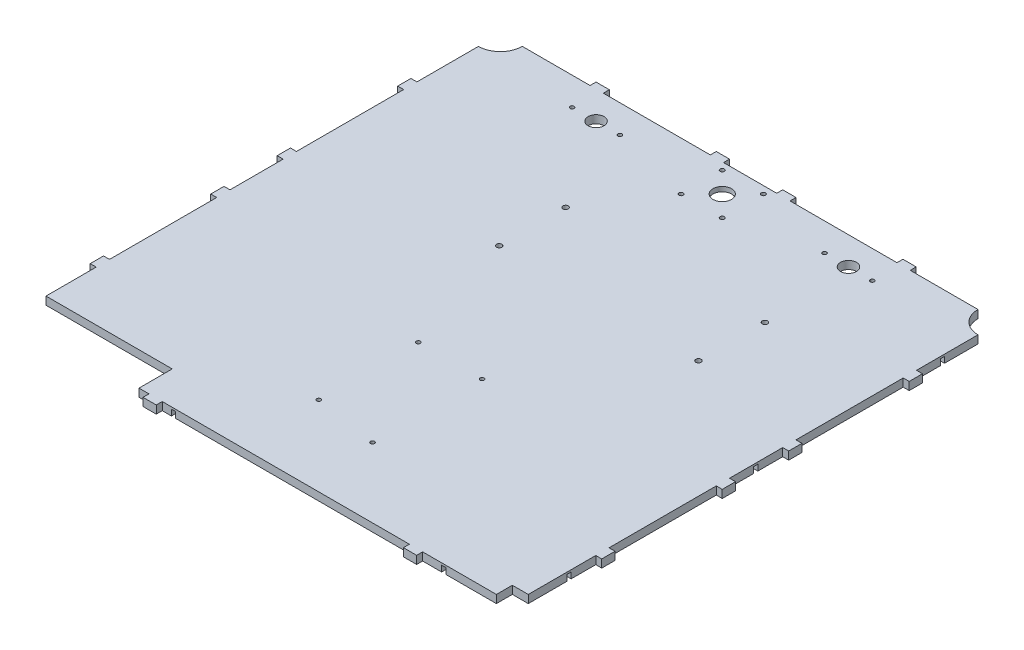
SolidWorks part; units mm, degrees
ref_plane "Alzado" through (0, 0, 0) normal (0, 0, 1) x (1, 0, 0)
ref_plane "Planta" through (0, 0, 0) normal (0, 1, 0) x (1, 0, 0)
ref_plane "Vista lateral" through (0, 0, 0) normal (1, 0, 0) x (0, 0, -1)
sketch "Croquis1" plane through (0, 0, 0) normal (0, 1, 0) x (1, 0, 0)
  line L0 (0, 0) -> (67.5, 0)
  line L1 (188, 367) -> (188, 375.2829) construction
  line L4 (77.5, 0) -> (102.5, 0)
  line L5 (0, 0) -> (0, 62.8)
  line L6 (0, 62.8) -> (-4.5, 62.8)
  line L7 (-4.5, 62.8) -> (-4.5, 72.8)
  line L8 (-4.5, 72.8) -> (0, 72.8)
  line L9 (0, 72.8) -> (0, 153.5)
  line L10 (0, 153.5) -> (-4.5, 153.5)
  line L11 (-4.5, 153.5) -> (-4.5, 163.5)
  line L12 (-4.5, 163.5) -> (0, 163.5)
  line L13 (0, 163.5) -> (0, 203.5)
  line L14 (0, 183.5) -> (180.5, 183.5) construction
  line L15 (188, 367) -> (188, 0) construction
  line L16 (-4.5, 203.5) -> (0, 203.5)
  line L17 (-4.5, 213.5) -> (-4.5, 203.5)
  line L18 (0, 213.5) -> (-4.5, 213.5)
  line L19 (0, 294.2) -> (0, 213.5)
  line L20 (-4.5, 294.2) -> (0, 294.2)
  line L21 (-4.5, 304.2) -> (-4.5, 294.2)
  line L22 (0, 304.2) -> (-4.5, 304.2)
  line L23 (0, 304.2) -> (0, 350.5)
  line L24 (16.5, 367) -> (67.5, 367)
  line L25 (67.5, 367) -> (67.5, 371.5)
  line L26 (67.5, 371.5) -> (77.5, 371.5)
  line L27 (77.5, 371.5) -> (77.5, 367)
  line L28 (77.5, 367) -> (158, 367)
  line L29 (158, 367) -> (158, 371.5)
  line L30 (158, 371.5) -> (168, 371.5)
  line L31 (168, 371.5) -> (168, 367)
  line L32 (168, 367) -> (208, 367)
  line L33 (376, 163.5) -> (376, 203.5)
  line L34 (380.5, 163.5) -> (376, 163.5)
  line L35 (380.5, 153.5) -> (380.5, 163.5)
  line L36 (376, 153.5) -> (380.5, 153.5)
  line L37 (376, 72.8) -> (376, 153.5)
  line L38 (380.5, 72.8) -> (376, 72.8)
  line L39 (380.5, 62.8) -> (380.5, 72.8)
  line L40 (376, 62.8) -> (380.5, 62.8)
  line L41 (376, 0) -> (376, 62.8)
  line L42 (298.5, -4.5) -> (298.5, 0)
  line L43 (308.5, -4.5) -> (298.5, -4.5)
  line L44 (308.5, 0) -> (308.5, -4.5)
  line L45 (376, 0) -> (308.5, 0)
  line L46 (208, 371.5) -> (208, 367)
  line L47 (218, 371.5) -> (208, 371.5)
  line L48 (218, 367) -> (218, 371.5)
  line L49 (298.5, 367) -> (218, 367)
  line L50 (298.5, 371.5) -> (298.5, 367)
  line L51 (308.5, 371.5) -> (298.5, 371.5)
  line L52 (308.5, 367) -> (308.5, 371.5)
  line L53 (359.5, 367) -> (308.5, 367)
  line L54 (376, 350.5) -> (376, 304.2)
  line L55 (376, 304.2) -> (380.5, 304.2)
  line L56 (380.5, 304.2) -> (380.5, 294.2)
  line L57 (380.5, 294.2) -> (376, 294.2)
  line L58 (376, 294.2) -> (376, 213.5)
  line L59 (376, 213.5) -> (380.5, 213.5)
  line L60 (380.5, 213.5) -> (380.5, 203.5)
  line L61 (380.5, 203.5) -> (376, 203.5)
  line L62 (102.5, 0) -> (102.5, 14.5062) construction
  line L63 (112.5, 0) -> (298.5, 0)
  line L64 (67.5, 0) -> (77.5, 0)
  line L65 (102.5, 0) -> (102.5, -4.5)
  line L66 (102.5, -4.5) -> (112.5, -4.5)
  line L67 (112.5, 0) -> (112.5, -4.5)
  arc A0 (0, 350.5) -> (16.5, 367) centre (0, 367) ccw
  arc A1 (376, 350.5) -> (359.5, 367) centre (376, 367) cw
  dimension "D8" = 33
  dimension "D14" = 46.3
  dimension "D2" = 20
  dimension "D5" = 62.8
  dimension "D6" = 4.5
  dimension "D7" = 10
  dimension "D9" = 10
  dimension "D10" = 20
  dimension "D11" = 51
  dimension "D12" = 10
  dimension "D13" = 4.5
  dimension "D15" = 10
  dimension "D16" = 16.5
  dimension "D17" = 16.5
  dimension "D18" = 25
  dimension "D19" = 10
extrude "Saliente-Extruir1" add sketch "Croquis1" against normal blind 6
sketch "Croquis3" plane through (0, -6, 0) normal (0, -1, 0) x (1, 0, 0)
  line L0 (324.3519, 0) -> (324.3519, -11.6932) construction
  line L1 (325.9019, -6.5002) -> (325.9019, 0)
  line L2 (327.1922, -8.0283) -> (327.1922, -9.5783)
  line L3 (322.2204, -10.8802) -> (322.3896, -10.8802)
  line L4 (325.9019, 0) -> (322.8019, 0)
  line L5 (321.5115, -8.0283) -> (321.5115, -9.5783)
  line L6 (326.4834, -10.8802) -> (326.3141, -10.8802)
  line L7 (322.8019, -6.5002) -> (322.8019, 0)
  line L9 (324.3519, -11.6932) -> (324.3519, 0.5178) construction
  line L10 (188, 0) -> (188, -367) construction
  line L11 (324.3519, -367) -> (324.3519, -355.3068) construction
  line L12 (208, -367) -> (168, -367) construction
  line L13 (322.8019, -360.4998) -> (322.8019, -367)
  line L14 (6.5002, -322.2809) -> (0, -322.2809)
  line L15 (8.7074, -321.1473) -> (10.2574, -321.1473)
  line L16 (10.8802, -326.1191) -> (10.8802, -326.1066)
  line L17 (0, -322.2809) -> (0, -325.5376)
  line L18 (8.0283, -326.828) -> (9.5783, -326.828)
  line L19 (10.8802, -321.6994) -> (10.8802, -321.8687)
  line L20 (321.5115, -358.9717) -> (321.5115, -357.4217)
  line L21 (6.5002, -325.5376) -> (0, -325.5376)
  line L22 (0, -42.91) -> (11.6932, -42.91) construction
  line L23 (6.5002, -41.36) -> (0, -41.36)
  line L24 (10.8802, -45.0415) -> (10.8802, -44.8722)
  line L25 (8.0283, -40.0697) -> (9.5783, -40.0697)
  line L26 (0, -44.46) -> (0, -41.36)
  line L27 (10.8802, -40.7785) -> (10.8802, -40.9478)
  line L28 (8.0283, -45.7503) -> (9.5783, -45.7503)
  line L29 (6.5002, -44.46) -> (0, -44.46)
  line L30 (326.4834, -356.1198) -> (326.3141, -356.1198)
  line L32 (121.0007, 0) -> (121.0007, -11.6932) construction
  line L33 (0, -183.2411) -> (376, -183.2411) construction
  line L34 (322.8019, -367) -> (325.9019, -367)
  line L35 (327.1922, -358.9717) -> (327.1922, -357.4217)
  line L36 (8.0283, -186.246) -> (9.5783, -186.246)
  line L37 (10.8802, -181.2741) -> (10.8802, -181.4434)
  line L38 (6.5002, -181.8556) -> (0, -181.8556)
  line L39 (6.5002, -184.9556) -> (0, -184.9556)
  line L40 (10.8802, -185.5371) -> (10.8802, -185.3679)
  line L41 (0, -183.4056) -> (11.6932, -183.4056) construction
  line L42 (0, -181.8556) -> (0, -184.9556)
  line L43 (8.0283, -180.5653) -> (9.5783, -180.5653)
  line L44 (122.5507, -6.5002) -> (122.5507, 0)
  line L45 (123.841, -8.0283) -> (123.841, -9.5783)
  line L46 (118.8692, -10.8802) -> (119.0384, -10.8802)
  line L47 (122.5507, 0) -> (119.4507, 0)
  line L48 (118.1603, -8.0283) -> (118.1603, -9.5783)
  line L49 (123.1322, -10.8802) -> (122.9629, -10.8802)
  line L50 (376, -42.7364) -> (364.3068, -42.7364) construction
  line L51 (369.4998, -44.2864) -> (376, -44.2864)
  line L52 (367.9717, -45.5768) -> (366.4217, -45.5768)
  line L53 (365.1198, -40.6049) -> (365.1198, -40.7742)
  line L54 (376, -44.2864) -> (376, -41.1864)
  line L55 (367.9717, -39.8961) -> (366.4217, -39.8961)
  line L56 (365.1198, -44.8679) -> (365.1198, -44.6987)
  line L57 (369.4998, -41.1864) -> (376, -41.1864)
  line L58 (376, -183.2411) -> (364.3068, -183.2411) construction
  line L59 (367.9717, -180.4008) -> (366.4217, -180.4008)
  line L60 (376, -181.6911) -> (376, -184.7911)
  line L61 (365.1198, -185.3726) -> (365.1198, -185.2033)
  line L62 (369.4998, -184.7911) -> (376, -184.7911)
  line L63 (369.4998, -181.6911) -> (376, -181.6911)
  line L64 (365.1198, -181.1096) -> (365.1198, -181.2788)
  line L65 (367.9717, -186.0814) -> (366.4217, -186.0814)
  line L66 (376, -323.728) -> (364.3068, -323.728) construction
  line L67 (369.4998, -325.278) -> (376, -325.278)
  line L68 (365.1198, -321.5965) -> (365.1198, -321.7657)
  line L69 (367.9717, -326.5683) -> (366.4217, -326.5683)
  line L70 (376, -322.178) -> (376, -325.278)
  line L71 (365.1198, -325.8594) -> (365.1198, -325.6902)
  line L72 (367.9717, -320.8876) -> (366.4217, -320.8876)
  line L73 (369.4998, -322.178) -> (376, -322.178)
  line L74 (324.3519, -355.9508) -> (324.3519, -367) construction
  line L75 (51.6481, -367) -> (51.6481, -355.3068) construction
  line L76 (50.0981, -360.4998) -> (50.0981, -367)
  line L77 (48.8078, -358.9717) -> (48.8078, -357.4217)
  line L78 (53.7796, -356.1198) -> (53.6104, -356.1198)
  line L79 (50.0981, -367) -> (53.1981, -367)
  line L80 (54.4885, -358.9717) -> (54.4885, -357.4217)
  line L81 (51.6481, -355.9508) -> (51.6481, -367) construction
  line L82 (51.6481, 0.5178) -> (51.6481, -24.8622) construction
  line L83 (322.2204, -356.1198) -> (322.3896, -356.1198)
  line L84 (119.4507, -6.5002) -> (119.4507, 0)
  line L85 (121.0007, -11.6932) -> (121.0007, 0) construction
  line L86 (325.9019, -360.4998) -> (325.9019, -367)
  line L87 (324.3519, -355.3068) -> (324.3519, -367.5178) construction
  line L88 (49.5166, -356.1198) -> (49.6859, -356.1198)
  line L89 (53.1981, -360.4998) -> (53.1981, -367)
  line L90 (51.6481, -355.3068) -> (51.6481, -367.5178) construction
  line L96 (51.6481, -355.9508) -> (51.6481, -367) construction
  arc A0 (327.1922, -8.0283) -> (325.9019, -6.5002) centre (325.6422, -8.0283) ccw
  arc A1 (322.3896, -10.8802) -> (326.3141, -10.8802) centre (324.3519, -8.9187) ccw
  arc A2 (322.2204, -10.8802) -> (321.5115, -9.5783) centre (323.0615, -9.5783) cw
  arc A3 (326.4834, -10.8802) -> (327.1922, -9.5783) centre (325.6422, -9.5783) ccw
  arc A4 (321.5115, -8.0283) -> (322.8019, -6.5002) centre (323.0615, -8.0283) cw
  arc A5 (8.7074, -321.1473) -> (6.5002, -322.2809) centre (8.0283, -322.5406) ccw
  arc A6 (10.8802, -326.1066) -> (10.8802, -321.8687) centre (8.9187, -323.9876) ccw
  arc A7 (10.8802, -326.1191) -> (9.5783, -326.828) centre (9.5783, -325.278) cw
  arc A8 (10.8802, -321.6994) -> (10.2574, -321.1473) centre (9.5783, -322.5406) ccw
  arc A9 (8.0283, -326.828) -> (6.5002, -325.5376) centre (8.0283, -325.278) cw
  arc A10 (8.0283, -40.0697) -> (6.5002, -41.36) centre (8.0283, -41.6197) ccw
  arc A11 (10.8802, -45.0415) -> (9.5783, -45.7503) centre (9.5783, -44.2003) cw
  arc A12 (10.8802, -40.7785) -> (9.5783, -40.0697) centre (9.5783, -41.6197) ccw
  arc A13 (10.8802, -40.9478) -> (10.8802, -44.8722) centre (8.9187, -42.91) cw
  arc A14 (8.0283, -45.7503) -> (6.5002, -44.46) centre (8.0283, -44.2003) cw
  arc A15 (8.0283, -180.5653) -> (6.5002, -181.8556) centre (8.0283, -182.1153) ccw
  arc A16 (8.0283, -186.246) -> (6.5002, -184.9556) centre (8.0283, -184.696) cw
  arc A17 (10.8802, -185.5371) -> (9.5783, -186.246) centre (9.5783, -184.696) cw
  arc A18 (10.8802, -181.2741) -> (9.5783, -180.5653) centre (9.5783, -182.1153) ccw
  arc A19 (10.8802, -185.3679) -> (10.8802, -181.4434) centre (8.9187, -183.4056) ccw
  arc A20 (123.841, -8.0283) -> (122.5507, -6.5002) centre (122.291, -8.0283) ccw
  arc A21 (119.0384, -10.8802) -> (122.9629, -10.8802) centre (121.0007, -8.9187) ccw
  arc A22 (118.8692, -10.8802) -> (118.1603, -9.5783) centre (119.7103, -9.5783) cw
  arc A23 (123.1322, -10.8802) -> (123.841, -9.5783) centre (122.291, -9.5783) ccw
  arc A24 (118.1603, -8.0283) -> (119.4507, -6.5002) centre (119.7103, -8.0283) cw
  arc A25 (367.9717, -45.5768) -> (369.4998, -44.2864) centre (367.9717, -44.0268) ccw
  arc A26 (365.1198, -40.7742) -> (365.1198, -44.6987) centre (367.0813, -42.7364) ccw
  arc A27 (365.1198, -40.6049) -> (366.4217, -39.8961) centre (366.4217, -41.4461) cw
  arc A28 (365.1198, -44.8679) -> (366.4217, -45.5768) centre (366.4217, -44.0268) ccw
  arc A29 (367.9717, -39.8961) -> (369.4998, -41.1864) centre (367.9717, -41.4461) cw
  arc A30 (365.1198, -185.2033) -> (365.1198, -181.2788) centre (367.0813, -183.2411) cw
  arc A31 (365.1198, -181.1096) -> (366.4217, -180.4008) centre (366.4217, -181.9508) cw
  arc A32 (365.1198, -185.3726) -> (366.4217, -186.0814) centre (366.4217, -184.5314) ccw
  arc A33 (367.9717, -186.0814) -> (369.4998, -184.7911) centre (367.9717, -184.5314) ccw
  arc A34 (367.9717, -180.4008) -> (369.4998, -181.6911) centre (367.9717, -181.9508) cw
  arc A35 (367.9717, -326.5683) -> (369.4998, -325.278) centre (367.9717, -325.0183) ccw
  arc A36 (365.1198, -321.5965) -> (366.4217, -320.8876) centre (366.4217, -322.4376) cw
  arc A37 (365.1198, -325.8594) -> (366.4217, -326.5683) centre (366.4217, -325.0183) ccw
  arc A38 (365.1198, -325.6902) -> (365.1198, -321.7657) centre (367.0813, -323.728) cw
  arc A39 (367.9717, -320.8876) -> (369.4998, -322.178) centre (367.9717, -322.4376) cw
  arc A40 (48.8078, -358.9717) -> (50.0981, -360.4998) centre (50.3578, -358.9717) ccw
  arc A41 (53.6104, -356.1198) -> (49.6859, -356.1198) centre (51.6481, -358.0813) ccw
  arc A42 (53.7796, -356.1198) -> (54.4885, -357.4217) centre (52.9385, -357.4217) cw
  arc A43 (49.5166, -356.1198) -> (48.8078, -357.4217) centre (50.3578, -357.4217) ccw
  arc A44 (54.4885, -358.9717) -> (53.1981, -360.4998) centre (52.9385, -358.9717) cw
  arc A50 (321.5115, -358.9717) -> (322.8019, -360.4998) centre (323.0615, -358.9717) ccw
  arc A51 (326.3141, -356.1198) -> (322.3896, -356.1198) centre (324.3519, -358.0813) ccw
  arc A52 (326.4834, -356.1198) -> (327.1922, -357.4217) centre (325.6422, -357.4217) cw
  arc A53 (322.2204, -356.1198) -> (321.5115, -357.4217) centre (323.0615, -357.4217) ccw
  arc A54 (327.1922, -358.9717) -> (325.9019, -360.4998) centre (325.6422, -358.9717) cw
  dimension "D17" = 4.38
  dimension "D21" = 1.55
  dimension "D23" = 6.5002
  dimension "D25" = 1.55
  dimension "D24" = 1.55
  dimension "D31" = 1.55
  dimension "D33" = 11.6932
  dimension "D15" = 1.55
  dimension "D18" = 0.4122
  dimension "D14" = 1.55
  dimension "D16" = 1.55
  dimension "D22" = 0.1692
  dimension "D26" = 1.55
  dimension "D20" = 1.5281
  dimension "D27" = 4.38
  dimension "D28" = 0.4122
  dimension "D29" = 1.55
  dimension "D30" = 1.5281
  dimension "D32" = 0.1692
  dimension "D34" = 51.6481
extrude "Cortar-Extruir1" cut sketch "Croquis3" against normal blind 4.5
sketch "Croquis5" plane through (0, 0, 0) normal (0, 1, 0) x (1, 0, 0)
  line L0 (188, 367) -> (188, 346) construction
  line L1 (0, 0) -> (12, 0)
  line L2 (0, 0) -> (0, 12)
  line L3 (0, 12) -> (12, 12)
  line L4 (12, 0) -> (12, 12)
  line L5 (376, 0) -> (364, 0)
  line L6 (376, 0) -> (376, 12)
  line L7 (376, 12) -> (364, 12)
  line L8 (364, 0) -> (364, 12)
  line L9 (158, 367) -> (77.5, 367) construction
  line L10 (67.5, 367) -> (16.5, 367) construction
  line L11 (208, 367) -> (168, 367) construction
  line L12 (172.5, 361.5) -> (172.5, 346) construction
  line L13 (172.5, 346) -> (188, 346) construction
  line L14 (188, 346) -> (73.5, 346) construction
  circle A0 centre (188, 346) radius 7
  circle A1 centre (172.5, 361.5) radius 1.6
  circle A2 centre (203.5, 361.5) radius 1.6
  circle A3 centre (203.5, 330.5) radius 1.6
  circle A4 centre (172.5, 330.5) radius 1.6
  circle A5 centre (93, 346) radius 6
  circle A6 centre (111, 346) radius 1.5
  circle A7 centre (75, 346) radius 1.5
  circle A8 centre (301, 346) radius 1.5
  circle A9 centre (265, 346) radius 1.5
  circle A10 centre (283, 346) radius 6
  dimension "D4" = 14
  dimension "D5" = 3.2
  dimension "D9" = 3
  dimension "D8" = 12
  dimension "D11" = 3
  dimension "D1" = 12
  dimension "D2" = 12
  dimension "D3" = 21
  dimension "D6" = 15.5
  dimension "D7" = 15.5
  dimension "D10" = 18
  dimension "D12" = 18
  dimension "D13" = 95
  dimension "D16" = 21
  dimension "D17" = 21
extrude "Cortar-Extruir2" cut sketch "Croquis5" against normal up to surface (6 mm away) up to face at (193.3495, -6, -193.3937)
sketch "Croquis7" plane through (0, 0, 0) normal (0, 1, 0) x (1, 0, 0)
  line L1 (12, 0) -> (102.5, 0) construction
  line L3 (95, 0) -> (0, 0)
  line L4 (95, 0) -> (95, 25)
  line L5 (95, 25) -> (0, 25)
  line L6 (0, 0) -> (0, 25)
  line L7 (0, 62.8) -> (0, 12) construction
  circle A0 centre (137.7441, 278.3503) radius 2
  circle A1 centre (137.7441, 228.3503) radius 2
  circle A2 centre (287.7441, 228.3503) radius 2
  circle A3 centre (287.7441, 278.3503) radius 2
  circle A4 centre (218.2736, 134.9894) radius 1.5
  circle A5 centre (170.2736, 134.9894) radius 1.5
  circle A6 centre (218.2736, 52.4894) radius 1.5
  circle A7 centre (170.2736, 59.9894) radius 1.5
  dimension "D5" = 4
  dimension "D6" = 4
  dimension "D7" = 4
  dimension "D8" = 4
  dimension "D1" = 3
  dimension "D4" = 3
  dimension "D10" = 3
  dimension "D12" = 3
  dimension "D2" = 50
  dimension "D3" = 50
  dimension "D9" = 48
  dimension "D11" = 82.5
  dimension "D13" = 75
  dimension "D14" = 95
  dimension "D15" = 25
  dimension "D16" = 150
extrude "Cortar-Extruir4" cut sketch "Croquis7" against normal blind 10
sketch "Croquis8" plane through (0, -6, 0) normal (0, -1, 0) x (1, 0, 0)
  circle A2 centre (265, -346) radius 1.5 construction
  circle A4 centre (188, -346) radius 7 construction
  circle A5 centre (188, -346) radius 7
  circle A6 centre (265, -346) radius 1.5
  circle A7 centre (188, -346) radius 11
  circle A8 centre (111, -346) radius 4.5
  circle A9 centre (75, -346) radius 4.5
  circle A10 centre (265, -346) radius 4.5
  circle A11 centre (301, -346) radius 4.5
  dimension "D1" = 95
  dimension "D2" = 95
extrude "Cortar-Extruir5" cut sketch "Croquis8" against normal blind 2.5
equation "\"Ancho_panel\"= 385'Ancho del panel"
equation "\"Alto_panel\"= 420'Alto del panel izquierdo"
equation "\"Altura_base_taladros\"= 70'Alto taladros de la base eje Z"
equation "\"Altura_superior_taladros\"= 8mm'Distancia taladros a top"
equation "\"Distancia_vert_entre_horizontales_ensambles\"= \"Alto_panel\" - \"Altura_base_taladros\" - \"Altura_superior_taladros\"'Distancia vertical entre horizontales de ensambles"
equation "\"Latrales_separacion_barras_a_escalon_bajo\"= 12.5'Separación entre las barras y el escalón inferior de la parte superior"
equation "\"Espacio_tensor_correa_motor\"= 8.5mm'Espacio para mover el motor en vertical y tensar la correa"
equation "\"Ancho_panel_interior\"= \"Ancho_panel\" - 9mm'Ancho panel interior"
equation "\"Fondo_panel_interior\"= \"Ancho_panel\" - 9mm'Fondo panel interior"
